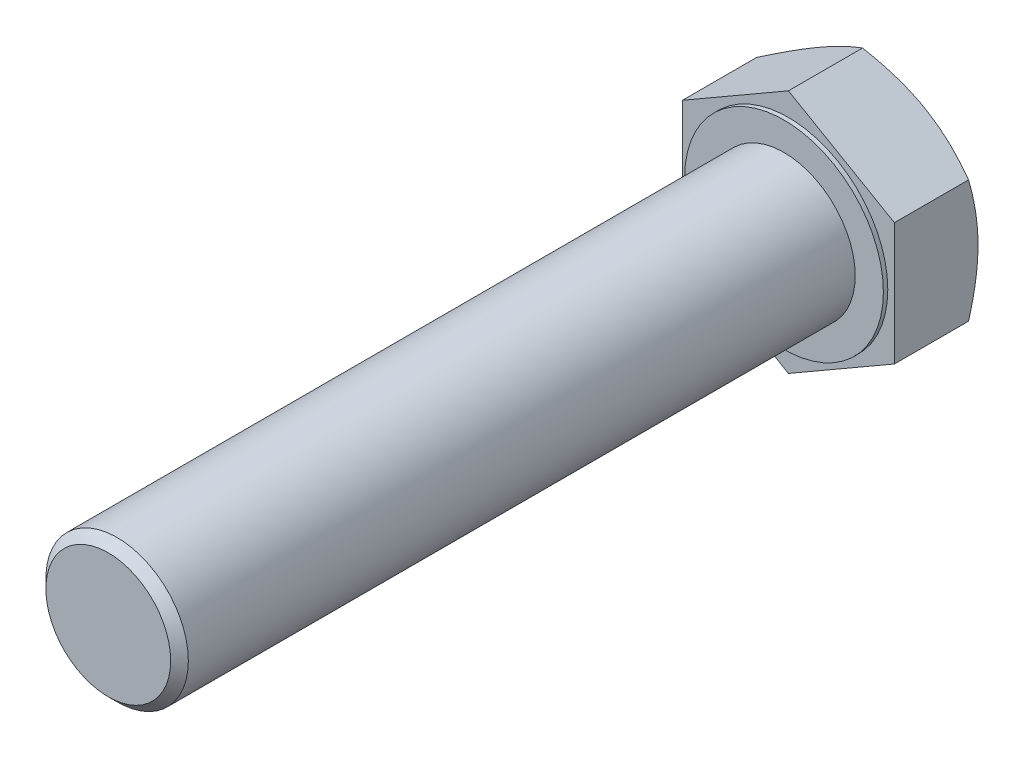
SolidWorks part; units mm, degrees
material "AISI 1010 Barra de acero laminada en caliente"
ref_plane "Alzado" through (0, 0, 0) normal (0, 0, 1) x (1, 0, 0)
ref_plane "Planta" through (0, 0, 0) normal (0, 1, 0) x (1, 0, 0)
ref_plane "Vista lateral" through (0, 0, 0) normal (1, 0, 0) x (0, 0, -1)
sketch "Croquis1" plane through (0, 0, 0) normal (0, 0, 1) x (1, 0, 0)
  line L1 (0, 13.8564) -> (-12, 6.9282)
  line L12 (-12, 6.9282) -> (-12, -6.9282)
  line L13 (-12, -6.9282) -> (0, -13.8564)
  line L14 (0, -13.8564) -> (12, -6.9282)
  line L15 (12, -6.9282) -> (12, 6.9282)
  line L16 (12, 6.9282) -> (0, 13.8564)
  circle A6 centre (0, 0) radius 12 construction
  dimension "D1" = 24
extrude "Saliente-Extruir1" add sketch "Croquis1" along normal blind 10
sketch "Croquis2" plane through (0, 0, 10) normal (0, 0, 1) x (1, 0, 0)
  circle A0 centre (0, 0) radius 8.0635
  dimension "D1" = 16.127
extrude "Saliente-Extruir2" add sketch "Croquis2" along normal blind 77
thread "Rosca1" pitch 1.5 start angle 0, offset 2, length 27, pitch 1.5, diameter 16.127
ref_plane "Plano1" through (-8.0635, 0, 89) normal (0, -1, 0) x (-1, 0, 0)
sketch "Perfil de rosca1" plane through (-8.0635, 0, 89) normal (0, -1, 0) x (-1, 0, 0)
  line L0 (0, 0) -> (0, 1.5) construction
  line L11 (0, 0) -> (0, 1.3125)
  line L12 (0, 1.3125) -> (-0.8119, 0.8437)
  line L13 (-0.8119, 0.8437) -> (-0.8119, 0.4687)
  line L15 (-0.8119, 0.4687) -> (0, 0)
  line L17 (-0.8119, 0.6562) -> (0, 0.6562) construction
  point P2 (0, 0)
  dimension "Pitch" = 1.5
  dimension "Profile_Angle" = 60
  dimension "Profile_Land" = 0.375
  dimension "Profile_Height" = 0.8119
sketch "Croquis7" plane through (0, 0, 0) normal (1, 0, 0) x (0, 0, -1)
  line L0 (-3.4955, 17.1228) -> (0.4663, 10.2607)
  line L1 (0.4663, 10.2607) -> (0.4663, 17.1228)
  line L2 (0.4663, 17.1228) -> (-3.4955, 17.1228)
  line L3 (-3.4955, 0) -> (3.749, 0) construction
  dimension "D1" = 30
revolve "Cortar-Revolución1" cut sketch "Croquis7" angle 360 about L3
sketch "Croquis8" plane through (0, 0, 10) normal (0, 0, 1) x (1, 0, 0)
  circle A0 centre (0, 0) radius 11.25
  dimension "D1" = 22.5
extrude "Saliente-Extruir3" add sketch "Croquis8" along normal blind 0.5
chamfer "Chaflán1" distance 1 angle 45 1 edges at (8.0635, 0, 87)
